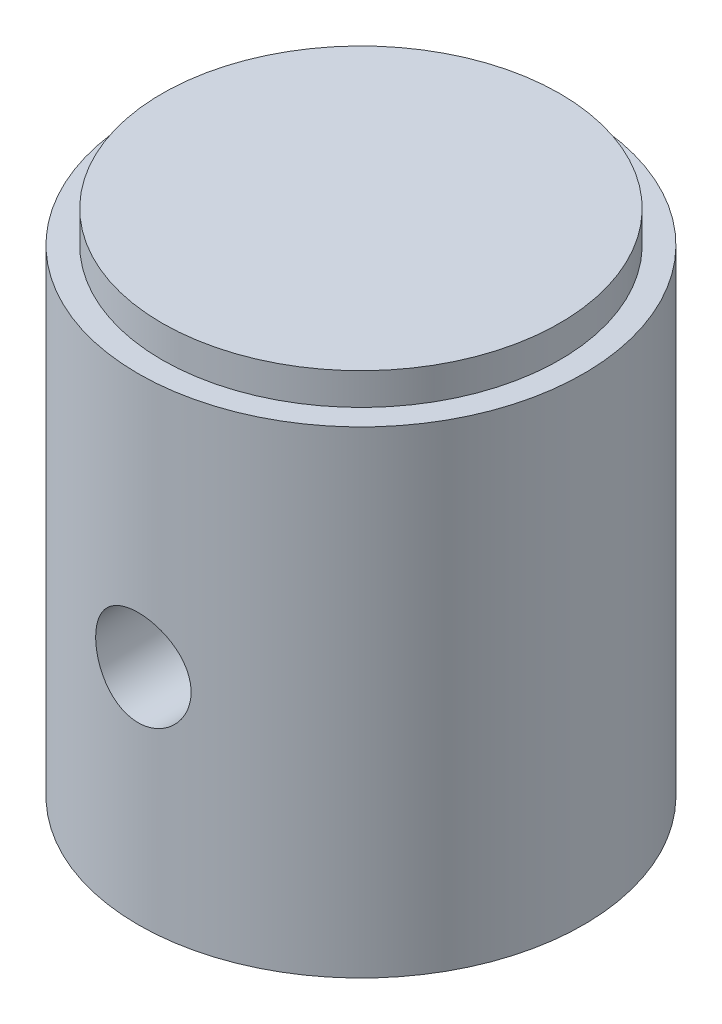
SolidWorks part; units mm, degrees
ref_plane "Front Plane" through (0, 0, 0) normal (0, 0, 1) x (1, 0, 0)
ref_plane "Top Plane" through (0, 0, 0) normal (0, 1, 0) x (1, 0, 0)
ref_plane "Right Plane" through (0, 0, 0) normal (1, 0, 0) x (0, 0, -1)
sketch "Sketch1" plane through (0, 0, 0) normal (0, 1, 0) x (1, 0, 0)
  circle A0 centre (0, 0) radius 7
  dimension "D1" = 14
extrude "Boss-Extrude1" add sketch "Sketch1" along normal blind 16
sketch "Sketch2" plane through (0, 0, 0) normal (0, 0, 1) x (1, 0, 0)
  line L0 (-7, 0) -> (7, 0) construction
  circle A0 centre (0, 7) radius 1.5
  dimension "D1" = 3
  dimension "D2" = 7
extrude "Cut-Extrude1" cut sketch "Sketch2" against normal through all and the other way through all
sketch "Sketch3" plane through (0, 0, 0) normal (0, -1, 0) x (1, 0, 0)
  circle A0 centre (0, 0) radius 4.75
  dimension "D1" = 9.5
extrude "Cut-Extrude2" cut sketch "Sketch3" against normal blind 11
sketch "Sketch4" plane through (0, 0, 0) normal (0, 0, 1) x (1, 0, 0)
  line L0 (0, 11) -> (0, 13.8541)
  line L1 (-4.75, 11) -> (4.75, 11) construction
  line L2 (0, 13.8541) -> (4.75, 11)
  line L3 (0, 11) -> (4.75, 11)
  dimension "D1" = 59
  dimension "D2" = 4.75
revolve "Cut-Revolve1" cut sketch "Sketch4" angle 360 about L0
sketch "Sketch5" plane through (0, 0, 0) normal (0, 0, 1) x (1, 0, 0)
  line L0 (4.75, 0) -> (4.75, 3.9838)
  line L1 (-7, 0) -> (7, 0) construction
  line L2 (-4.75, 0) -> (4.75, 0) construction
  line L3 (4.75, 3.9838) -> (6.2, 0)
  line L4 (6.2, 0) -> (4.75, 0)
  line L5 (0, 0) -> (0, 6.4279) construction
  dimension "D1" = 1.45
  dimension "D2" = 20
revolve "Cut-Revolve2" cut sketch "Sketch5" angle 360 about L5
sketch "Sketch6" plane through (0, 16, 0) normal (0, 1, 0) x (1, 0, 0)
  circle A0 centre (0, 0) radius 6.25
  circle A1 centre (0, 0) radius 7
  dimension "D1" = 12.5
extrude "Cut-Extrude3" cut sketch "Sketch6" against normal blind 1
